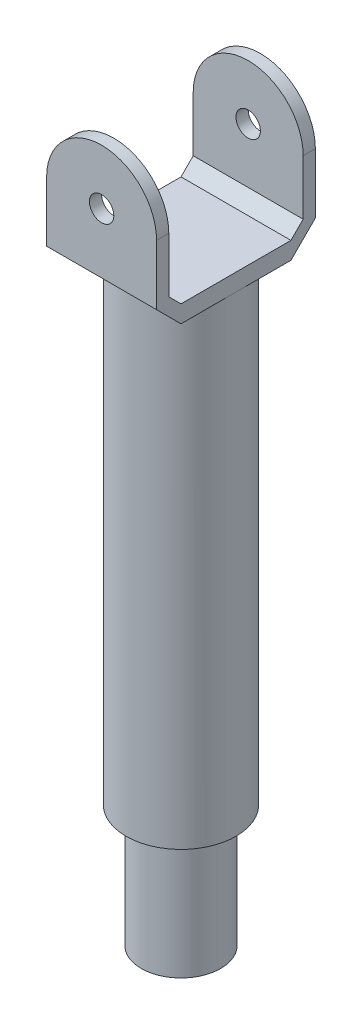
SolidWorks part; units mm, degrees
ref_plane "Front Plane" through (0, 0, 0) normal (0, 0, 1) x (1, 0, 0)
ref_plane "Top Plane" through (0, 0, 0) normal (0, 1, 0) x (1, 0, 0)
ref_plane "Right Plane" through (0, 0, 0) normal (1, 0, 0) x (0, 0, -1)
sketch "Sketch1" plane through (0, 0, 0) normal (0, 1, 0) x (1, 0, 0)
  circle A0 centre (0, 0) radius 32.5
  dimension "D1" = 65
extrude "Boss-Extrude1" add sketch "Sketch1" along normal blind 100
sketch "Sketch2" plane through (0, 100, 0) normal (0, 1, 0) x (1, 0, 0)
  circle A0 centre (0, 0) radius 45
  dimension "D1" = 90
extrude "Boss-Extrude2" add sketch "Sketch2" along normal blind 400
sketch "Sketch6" plane through (0, 0, 0) normal (1, 0, 0) x (0, 0, -1)
  line L0 (-45, 500) -> (-55, 510)
  line L1 (-55, 510) -> (-55, 600)
  line L2 (-55, 600) -> (-65, 600)
  line L3 (-65, 600) -> (-65, 505.8579)
  line L4 (-65, 505.8579) -> (-45, 485.8579)
  line L5 (-45, 500) -> (-45, 100) construction
  line L6 (-45, 485.8579) -> (45, 485.8579)
  line L7 (45, 100) -> (45, 500) construction
  line L8 (45, 485.8579) -> (65, 505.8579)
  line L9 (65, 505.8579) -> (65, 600)
  line L10 (65, 600) -> (55, 600)
  line L11 (55, 600) -> (55, 510)
  line L12 (55, 510) -> (45, 500)
  line L13 (45, 500) -> (-45, 500)
  dimension "D1" = 135
  dimension "D2" = 90
  dimension "D3" = 10
  dimension "D4" = 10
  dimension "D5" = 10
extrude "Boss-Extrude3" add sketch "Sketch6" along normal mid plane 90
sketch "Sketch7" plane through (0, 0, 65) normal (0, 0, 1) x (1, 0, 0)
  line L0 (-45, 600) -> (-45, 505.8579) construction
  line L1 (45, 600) -> (-45, 600) construction
  line L2 (45, 600) -> (45, 505.8579) construction
  line L3 (-45, 555) -> (-45, 605)
  line L4 (-45, 605) -> (45, 605)
  line L5 (45, 605) -> (45, 555)
  circle A0 centre (0, 555) radius 10
  arc A1 (45, 555) -> (-45, 555) centre (0, 555) ccw
  dimension "D1" = 5
  dimension "D2" = 20
extrude "Cut-Extrude2" cut sketch "Sketch7" against normal through all both and the other way through all
